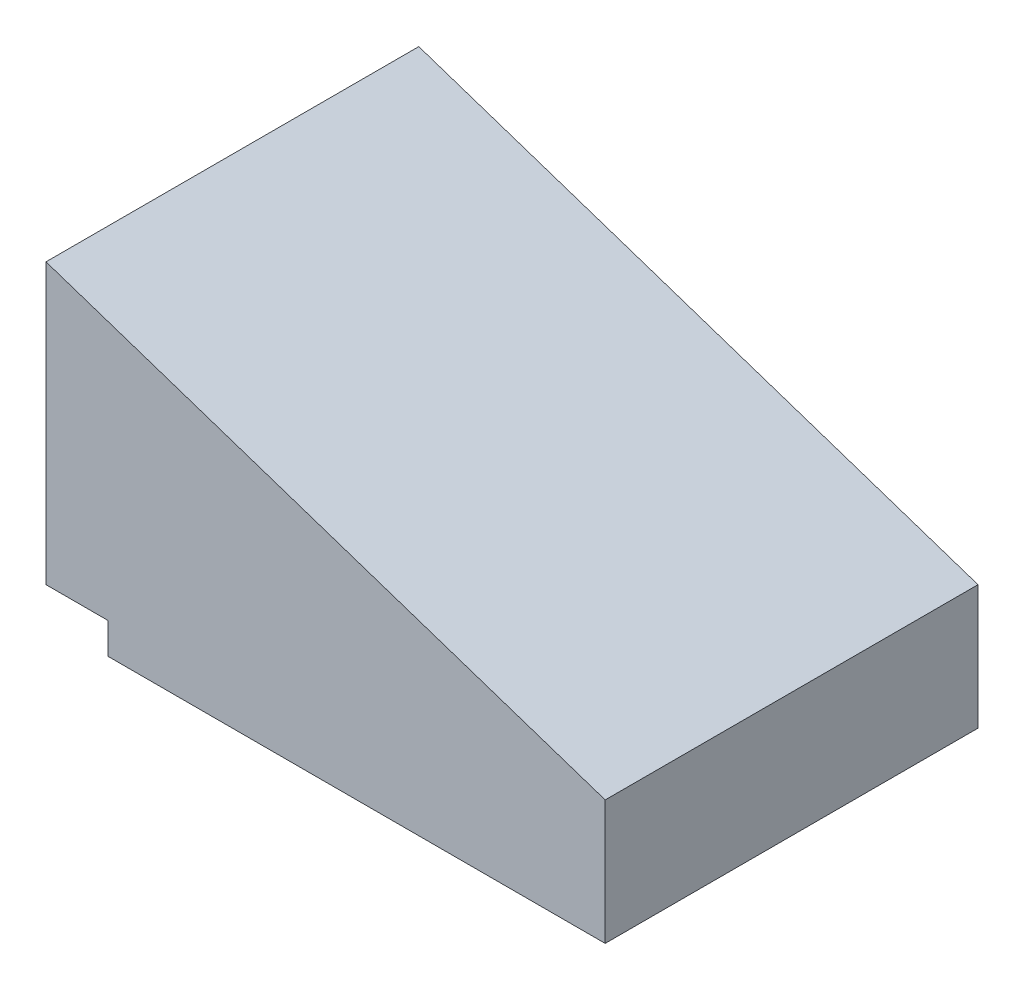
SolidWorks part; units mm, degrees
material "Acrylic (Medium-high impact)"
ref_plane "Front Plane" through (0, 0, 0) normal (0, 0, 1) x (1, 0, 0)
ref_plane "Top Plane" through (0, 0, 0) normal (0, 1, 0) x (1, 0, 0)
ref_plane "Right Plane" through (0, 0, 0) normal (1, 0, 0) x (0, 0, -1)
sketch "Sketch3" plane through (0, 0, 0) normal (0, 0, 1) x (1, 0, 0)
  line L0 (-228.6, 127) -> (0, 50.8)
  line L1 (0, 0) -> (-228.6, 0)
  line L2 (0, 0) -> (0, 50.8)
  line L4 (-228.6, 0) -> (-228.6, 127)
  dimension "D1" = 50.8
  dimension "D2" = 127
  dimension "D3" = 228.6
extrude "Boss-Extrude2" add sketch "Sketch3" along normal blind 152.4
shell "Shell1" thickness 1.5875
sketch "Sketch4" plane through (0, 0, 0) normal (0, 0, -1) x (-1, 0, 0)
  line L1 (228.6, 0) -> (203.2, 0)
  line L2 (228.6, 0) -> (228.6, 12.7)
  line L3 (228.6, 12.7) -> (203.2, 12.7)
  line L4 (203.2, 0) -> (203.2, 12.7)
  dimension "D1" = 12.7
  dimension "D2" = 25.4
extrude "Cut-Extrude1" cut sketch "Sketch4" against normal blind 152.4
